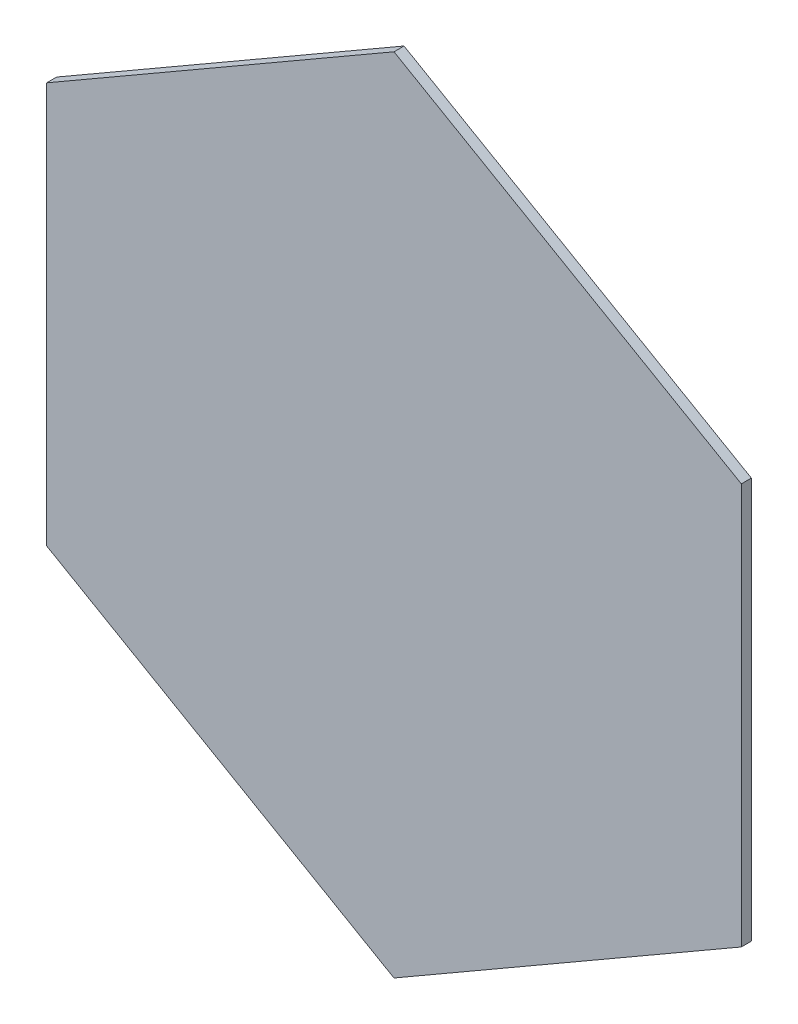
SolidWorks part; units mm, degrees
ref_plane "Plano frontal" through (0, 0, 0) normal (0, 0, 1) x (1, 0, 0)
ref_plane "Plano superior" through (0, 0, 0) normal (0, 1, 0) x (1, 0, 0)
ref_plane "Plano direito" through (0, 0, 0) normal (1, 0, 0) x (0, 0, -1)
sketch "Esboço1" plane through (0, 0, 0) normal (0, 0, 1) x (1, 0, 0)
  line L1 (0, 120) -> (-103.923, 60)
  line L2 (-103.923, 60) -> (-103.923, -60)
  line L3 (-103.923, -60) -> (0, -120)
  line L4 (0, -120) -> (103.923, -60)
  line L5 (103.923, -60) -> (103.923, 60)
  line L6 (103.923, 60) -> (0, 120)
  circle A0 centre (0, 0) radius 103.923 construction
  dimension "D1" = 120
extrude "Ressalto-extrusão1" add sketch "Esboço1" along normal blind 3
